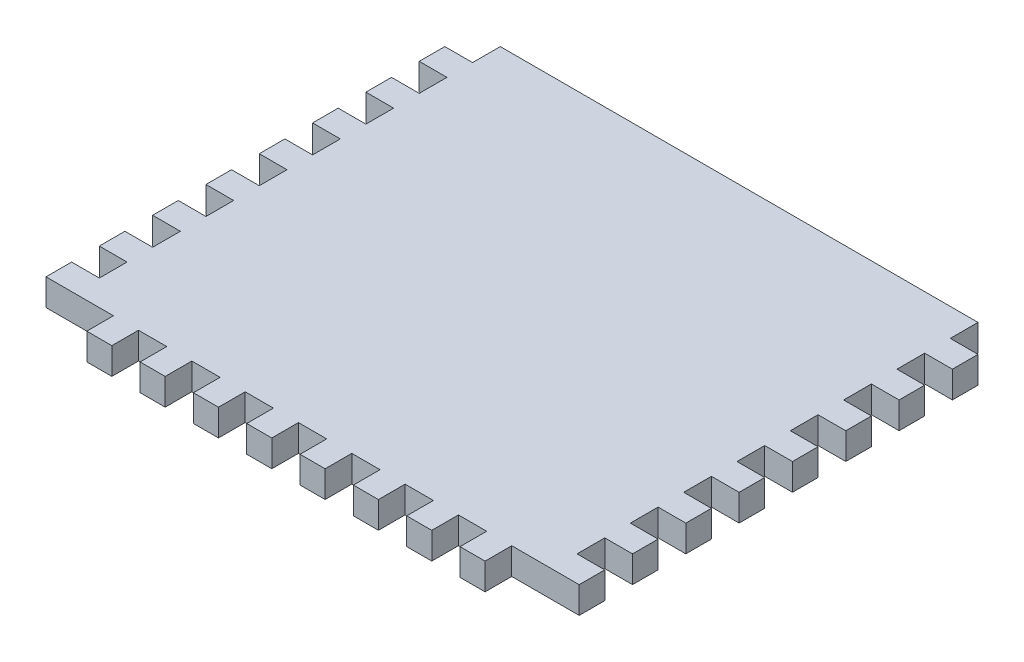
SolidWorks part; units mm, degrees
ref_plane "Front Plane" through (0, 0, 0) normal (0, 0, 1) x (1, 0, 0)
ref_plane "Top Plane" through (0, 0, 0) normal (0, 1, 0) x (1, 0, 0)
ref_plane "Right Plane" through (0, 0, 0) normal (1, 0, 0) x (0, 0, -1)
sketch "Sketch1" plane through (0, 0, 0) normal (0, 1, 0) x (1, 0, 0)
  line L1 (-63.5, -53.975) -> (63.5, -53.975)
  line L2 (-63.5, -53.975) -> (-63.5, 53.975)
  line L3 (-63.5, 53.975) -> (63.5, 53.975)
  line L4 (63.5, -53.975) -> (63.5, 53.975)
  line L5 (-63.5, -53.975) -> (63.5, 53.975) construction
  line L6 (-63.5, 53.975) -> (63.5, -53.975) construction
  point P0 (0, 0)
  dimension "D1" = 127
  dimension "D2" = 107.95
extrude "Boss-Extrude1" add sketch "Sketch1" along normal blind 6.35
sketch "Sketch2" plane through (0, 0, 0) normal (0, -1, 0) x (1, 0, 0)
  line L0 (-34.7345, 47.625) -> (-41.4655, 47.625)
  line L5 (63.5, 53.975) -> (63.5, -53.975) construction
  line L34 (0, 0) -> (0, -14.8721) construction
  line L39 (63.5, 41.529) -> (56.896, 41.529)
  line L41 (63.5, 54.229) -> (63.5, 47.625)
  line L42 (63.5, 47.625) -> (56.896, 47.625)
  line L44 (63.5, 41.529) -> (63.5, 34.925)
  line L45 (63.5, 34.925) -> (56.896, 34.925)
  line L46 (56.896, 41.529) -> (56.896, 34.925)
  line L47 (63.5, 28.829) -> (56.896, 28.829)
  line L48 (63.5, 28.829) -> (63.5, 22.225)
  line L49 (63.5, 22.225) -> (56.896, 22.225)
  line L50 (56.896, 28.829) -> (56.896, 22.225)
  line L51 (63.5, 16.129) -> (56.896, 16.129)
  line L52 (63.5, 16.129) -> (63.5, 9.525)
  line L53 (63.5, 9.525) -> (56.896, 9.525)
  line L54 (56.896, 16.129) -> (56.896, 9.525)
  line L55 (63.5, 3.429) -> (56.896, 3.429)
  line L56 (63.5, 3.429) -> (63.5, -3.175)
  line L57 (63.5, -3.175) -> (56.896, -3.175)
  line L58 (56.896, 3.429) -> (56.896, -3.175)
  line L59 (63.5, -9.271) -> (56.896, -9.271)
  line L60 (63.5, -9.271) -> (63.5, -15.875)
  line L61 (63.5, -15.875) -> (56.896, -15.875)
  line L62 (56.896, -9.271) -> (56.896, -15.875)
  line L63 (63.5, -21.971) -> (56.896, -21.971)
  line L64 (63.5, -21.971) -> (63.5, -28.575)
  line L65 (63.5, -28.575) -> (56.896, -28.575)
  line L66 (56.896, -21.971) -> (56.896, -28.575)
  line L67 (63.5, -34.671) -> (56.896, -34.671)
  line L68 (63.5, -34.671) -> (63.5, -41.275)
  line L69 (63.5, -41.275) -> (56.896, -41.275)
  line L70 (56.896, -34.671) -> (56.896, -41.275)
  line L71 (-56.896, -34.671) -> (-56.896, -41.275)
  line L72 (-63.5, -41.275) -> (-56.896, -41.275)
  line L73 (-63.5, -34.671) -> (-63.5, -41.275)
  line L74 (-63.5, -34.671) -> (-56.896, -34.671)
  line L75 (-56.896, -21.971) -> (-56.896, -28.575)
  line L76 (-63.5, -28.575) -> (-56.896, -28.575)
  line L77 (-63.5, -21.971) -> (-63.5, -28.575)
  line L78 (-63.5, -21.971) -> (-56.896, -21.971)
  line L79 (-56.896, -9.271) -> (-56.896, -15.875)
  line L80 (-63.5, -15.875) -> (-56.896, -15.875)
  line L81 (-63.5, -9.271) -> (-63.5, -15.875)
  line L82 (-63.5, -9.271) -> (-56.896, -9.271)
  line L83 (-56.896, 3.429) -> (-56.896, -3.175)
  line L84 (-63.5, -3.175) -> (-56.896, -3.175)
  line L85 (-63.5, 3.429) -> (-63.5, -3.175)
  line L86 (-63.5, 3.429) -> (-56.896, 3.429)
  line L87 (-56.896, 16.129) -> (-56.896, 9.525)
  line L88 (-63.5, 9.525) -> (-56.896, 9.525)
  line L89 (-63.5, 16.129) -> (-63.5, 9.525)
  line L90 (-63.5, 16.129) -> (-56.896, 16.129)
  line L91 (-56.896, 28.829) -> (-56.896, 22.225)
  line L92 (-63.5, 22.225) -> (-56.896, 22.225)
  line L93 (-63.5, 28.829) -> (-63.5, 22.225)
  line L94 (-63.5, 28.829) -> (-56.896, 28.829)
  line L95 (-56.896, 41.529) -> (-56.896, 34.925)
  line L96 (-63.5, 34.925) -> (-56.896, 34.925)
  line L97 (-63.5, 41.529) -> (-63.5, 34.925)
  line L99 (-63.5, 47.625) -> (-56.896, 47.625)
  line L100 (-63.5, 54.229) -> (-63.5, 47.625)
  line L102 (-63.5, 41.529) -> (-56.896, 41.529)
  line L103 (56.896, 47.625) -> (47.4345, 47.625)
  line L104 (34.7345, 47.625) -> (34.7345, 54.229)
  line L106 (34.7345, 54.229) -> (28.7655, 54.229)
  line L107 (28.7655, 54.229) -> (28.7655, 47.625)
  line L108 (28.7655, 47.625) -> (22.0345, 47.625)
  line L109 (22.0345, 47.625) -> (22.0345, 54.229)
  line L110 (22.0345, 54.229) -> (16.0655, 54.229)
  line L111 (16.0655, 54.229) -> (16.0655, 47.625)
  line L112 (16.0655, 47.625) -> (9.3345, 47.625)
  line L113 (9.3345, 47.625) -> (9.3345, 54.229)
  line L114 (9.3345, 54.229) -> (3.3655, 54.229)
  line L115 (3.3655, 54.229) -> (3.3655, 47.625)
  line L116 (3.3655, 47.625) -> (-3.3655, 47.625)
  line L117 (-3.3655, 47.625) -> (-3.3655, 54.229)
  line L118 (-3.3655, 54.229) -> (-9.3345, 54.229)
  line L119 (-9.3345, 54.229) -> (-9.3345, 47.625)
  line L120 (-9.3345, 47.625) -> (-16.0655, 47.625)
  line L121 (-16.0655, 47.625) -> (-16.0655, 54.229)
  line L122 (-16.0655, 54.229) -> (-22.0345, 54.229)
  line L123 (-22.0345, 54.229) -> (-22.0345, 47.625)
  line L124 (-22.0345, 47.625) -> (-28.7655, 47.625)
  line L125 (-28.7655, 47.625) -> (-28.7655, 54.229)
  line L126 (-28.7655, 54.229) -> (-34.7345, 54.229)
  line L127 (-34.7345, 54.229) -> (-34.7345, 47.625)
  line L137 (-63.5, 54.229) -> (-63.5, 63.0316)
  line L138 (63.5, -53.975) -> (-63.5, -53.975) construction
  line L139 (-63.5, 63.0316) -> (63.5, 63.0316)
  line L140 (63.5, 63.0316) -> (63.5, 54.229)
  line L141 (63.5, -47.371) -> (63.5, -53.975)
  line L142 (63.5, -53.975) -> (56.896, -53.975)
  line L143 (56.896, -53.975) -> (56.896, -47.371)
  line L144 (56.896, -47.371) -> (63.5, -47.371)
  line L145 (-56.896, -47.371) -> (-63.5, -47.371)
  line L146 (-56.896, -53.975) -> (-56.896, -47.371)
  line L147 (-63.5, -53.975) -> (-56.896, -53.975)
  line L148 (-63.5, -47.371) -> (-63.5, -53.975)
  line L149 (-63.5, -53.975) -> (-63.5, 53.975) construction
  line L150 (63.5, 53.975) -> (63.5, -53.975) construction
  line L151 (41.4655, 47.625) -> (41.4655, 54.229)
  line L152 (41.4655, 54.229) -> (47.4345, 54.229)
  line L153 (47.4345, 54.229) -> (47.4345, 47.625)
  line L154 (-41.4655, 47.625) -> (-41.4655, 54.229)
  line L155 (-41.4655, 54.229) -> (-47.4345, 54.229)
  line L156 (-47.4345, 54.229) -> (-47.4345, 47.625)
  line L157 (-47.4345, 47.625) -> (-56.896, 47.625)
  line L158 (41.4655, 47.625) -> (34.7345, 47.625)
  point P3 (0, 47.625)
  dimension "D2" = 6.604
  dimension "D3" = 5.969
  dimension "D6" = 6.731
  dimension "D8" = 6.604
  dimension "D9" = 9
extrude "Cut-Extrude1" cut sketch "Sketch2" against normal through all
